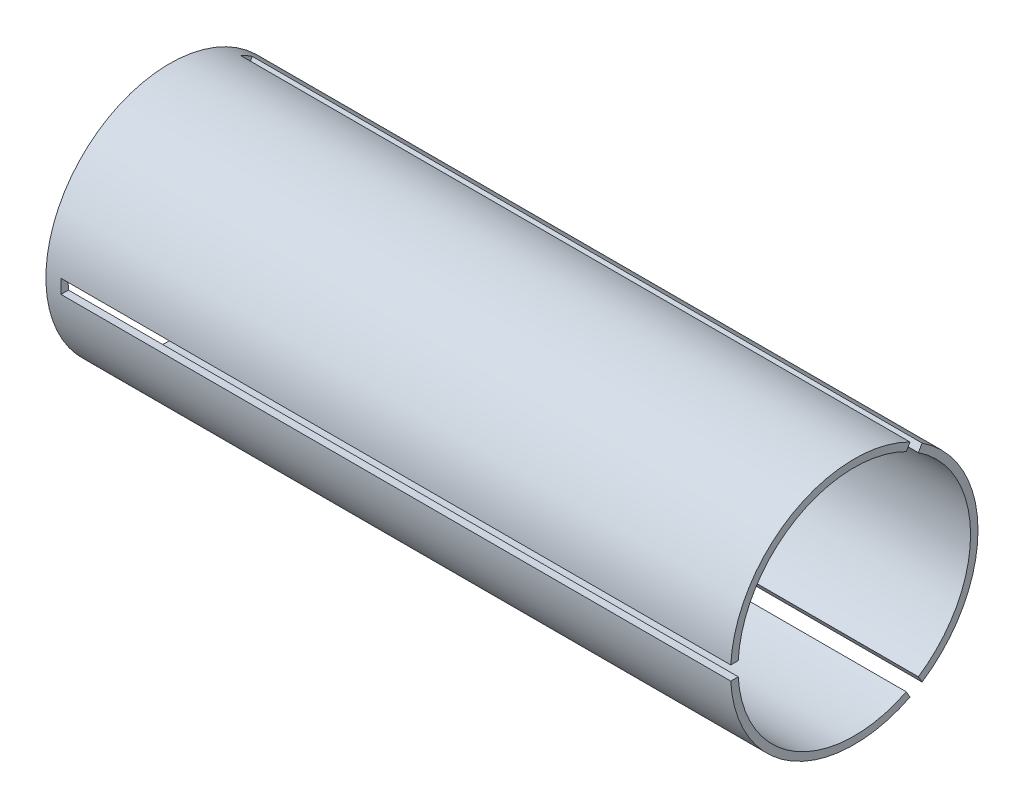
SolidWorks part; units mm, degrees
ref_plane "Front Plane" through (0, 0, 0) normal (1, 0, 0) x (0, 1, 0)
ref_plane "Top Plane" through (0, 0, 0) normal (0, 0, 1) x (0, 1, 0)
ref_plane "Right Plane" through (0, 0, 0) normal (0, 1, 0) x (-1, 0, 0)
sketch "Sketch1" plane through (0, 0, 0) normal (1, 0, 0) x (0, 1, 0)
  circle A0 centre (0, 0) radius 39.6875
  circle A1 centre (0, 0) radius 42.2275
  dimension "D1" = 79.375
  dimension "D2" = 2.54
extrude "Boss-Extrude1" add sketch "Sketch1" along normal blind 233.68
sketch "Sketch2" plane through (0, 0, 0) normal (0, 0, 1) x (0, 1, 0)
  line L0 (-42.2275, -233.68) -> (42.2275, -233.68) construction
  line L1 (-2.3813, -5.08) -> (2.3812, -5.08)
  line L2 (-2.3813, -5.08) -> (-2.3813, -233.68)
  line L3 (-2.3813, -233.68) -> (2.3812, -233.68)
  line L4 (2.3812, -5.08) -> (2.3812, -233.68)
  line L5 (-2.3813, -5.08) -> (2.3812, -233.68) construction
  line L6 (-2.3813, -233.68) -> (2.3812, -5.08) construction
  point P0 (0, -119.38)
  dimension "D1" = 4.7625
  dimension "D2" = 228.6
extrude "Cut-Extrude1" cut sketch "Sketch2" along normal through all
pattern_circular "CirPattern1" count 3 over 360 about axis through (0, 0, 0) along (1, 0, 0) of "Cut-Extrude1"
